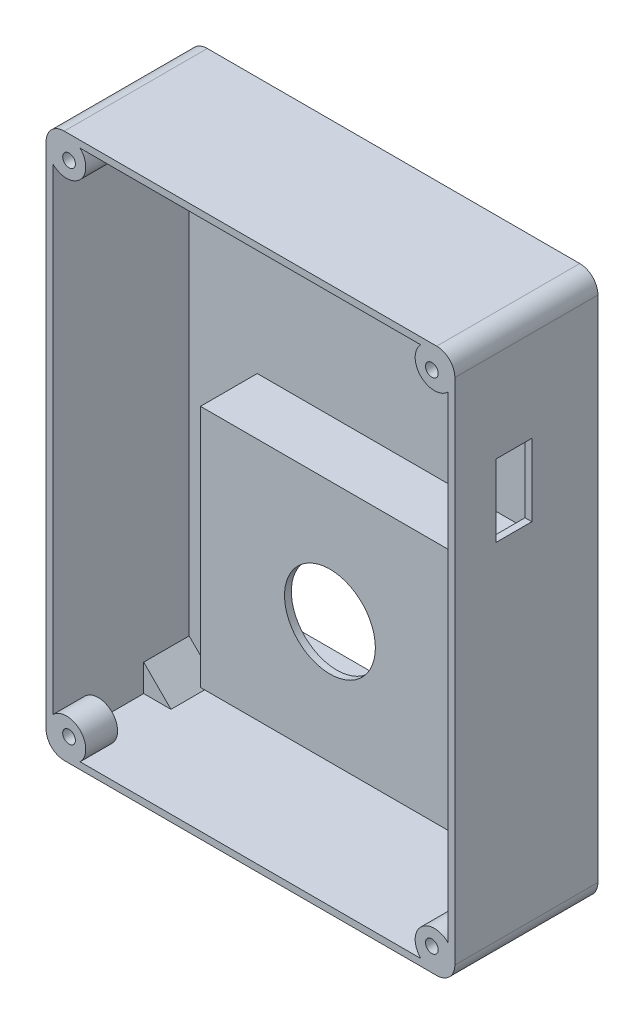
SolidWorks part; units mm, degrees
ref_plane "Front Plane" through (0, 0, 0) normal (0, 0, 1) x (1, 0, 0)
ref_plane "Top Plane" through (0, 0, 0) normal (0, 1, 0) x (1, 0, 0)
ref_plane "Right Plane" through (0, 0, 0) normal (1, 0, 0) x (0, 0, -1)
sketch "Sketch2" plane through (0, 0, 0) normal (0, 0, 1) x (1, 0, 0)
  line L1 (-45, -60) -> (45, -60)
  line L2 (-45, -60) -> (-45, 60)
  line L3 (-45, 60) -> (45, 60)
  line L4 (45, -60) -> (45, 60)
  line L5 (-45, -60) -> (45, 60) construction
  line L6 (-45, 60) -> (45, -60) construction
  point P0 (0, 0)
extrude "Boss-Extrude1" add sketch "Sketch2" along normal blind 31.5
sketch "Sketch4" plane through (0, 0, 31.5) normal (0, 0, 1) x (1, 0, 0)
  line L1 (-43.5, -58.5) -> (43.5, -58.5)
  line L2 (-43.5, -58.5) -> (-43.5, 58.5)
  line L3 (-43.5, 58.5) -> (43.5, 58.5)
  line L4 (43.5, -58.5) -> (43.5, 58.5)
  line L5 (-43.5, -58.5) -> (43.5, 58.5) construction
  line L6 (-43.5, 58.5) -> (43.5, -58.5) construction
  point P0 (0, 0)
extrude "Cut-Extrude1" cut sketch "Sketch4" against normal blind 30
fillet "Fillet4" radius 4 4 edges at (45, -60, 15.75) (-45, -60, 15.75) (45, 60, 15.75) (-45, 60, 15.75)
ref_plane "Plane1" through (0, 0, 0) normal (1, 0, 0) x (0, 0, -1)
ref_plane "Plane2" through (0, 0, 0) normal (0, 1, 0) x (1, 0, 0)
sketch "Sketch18" plane through (0, 0, 1.5) normal (0, 0, 1) x (1, 0, 0)
  line L0 (0, -58.5) -> (0, -48.5)
  line L1 (-43.5, -58.5) -> (43.5, -58.5) construction
  line L2 (0, -16.5) -> (0, 16.5) construction
  line L3 (0, -48.5) -> (0, -21.7755)
  line L5 (-28.5, -48.5755) -> (28.5, -48.5755)
  line L6 (-28.5, -48.5755) -> (-28.5, 5.0245)
  line L7 (-28.5, 5.0245) -> (28.5, 5.0245)
  line L8 (28.5, -48.5755) -> (28.5, 5.0245)
  line L9 (-28.5, -48.5755) -> (28.5, 5.0245) construction
  line L10 (-28.5, 5.0245) -> (28.5, -48.5755) construction
extrude "khay_pin" add sketch "Sketch18" along normal blind 12.5
sketch "Sketch21" plane through (0, 0, 14) normal (0, 0, 1) x (1, 0, 0)
  line L0 (-28.5, -21.7755) -> (28.5, -21.7755) construction
  line L1 (-28.5, -48.5755) -> (-28.5, 5.0245) construction
  line L2 (28.5, -48.5755) -> (28.5, 5.0245) construction
  line L4 (-26.5, -46.5755) -> (26.5, -46.5755)
  line L5 (-26.5, -46.5755) -> (-26.5, 3.0245)
  line L6 (-26.5, 3.0245) -> (26.5, 3.0245)
  line L7 (26.5, -46.5755) -> (26.5, 3.0245)
  line L8 (-26.5, -46.5755) -> (26.5, 3.0245) construction
  line L9 (-26.5, 3.0245) -> (26.5, -46.5755) construction
  point P6 (0, -21.7755)
extrude "Boss-Extrude11" add sketch "Sketch21" against normal blind 15
sketch "Sketch22" plane through (0, 0, -1) normal (0, 0, -1) x (-1, 0, 0)
  line L0 (-26.5, -21.7755) -> (26.5, -21.7755) construction
  line L1 (-26.5, -46.5755) -> (-26.5, 3.0245) construction
  line L2 (26.5, 3.0245) -> (26.5, -46.5755) construction
  line L4 (-26.5, -46.5755) -> (26.5, -46.5755)
  line L5 (-26.5, -46.5755) -> (-26.5, 3.0245)
  line L6 (-26.5, 3.0245) -> (26.5, 3.0245)
  line L7 (26.5, -46.5755) -> (26.5, 3.0245)
  line L8 (-26.5, -46.5755) -> (26.5, 3.0245) construction
  line L9 (-26.5, 3.0245) -> (26.5, -46.5755) construction
  point P6 (0, -21.7755)
extrude "Cut-Extrude4" cut sketch "Sketch22" against normal blind 13.5
sketch "Sketch30" plane through (26.5, 0, 0) normal (-1, 0, 0) x (0, 0, 1)
  line L0 (0, 3.0245) -> (12.5, 3.0245)
  line L1 (12.5, 3.0245) -> (12.5, -1.9755)
  line L2 (12.5, -1.9755) -> (12.5, -15.9755)
  line L3 (12.5, -1.9755) -> (5.5, -1.9755)
  line L4 (12.5, -15.9755) -> (5.5, -15.9755)
  line L5 (5.5, -1.9755) -> (5.5, -15.9755)
  line L6 (12.5, 3.0245) -> (12.5, -46.5755) construction
  line M3 (12.5, -46.5755) -> (12.5, 3.0245)
extrude "Cut-Extrude8" cut sketch "Sketch30" against normal blind 5 contours L3 L5 L4 M3
sketch "Sketch34" plane through (0, 0, 31.5) normal (0, 0, 1) x (1, 0, 0)
  line L0 (-43.5, 58.5) -> (-40.5, 58.5)
  line L1 (43.5, 58.5) -> (-43.5, 58.5) construction
  line L2 (-40.5, 58.5) -> (-40.5, 55.5)
  circle A0 centre (-40.5, 55.5) radius 4.2426
extrude "Boss-Extrude12" add sketch "Sketch34" against normal blind 7
sketch "Sketch37" plane through (45, 0, 0) normal (1, 0, 0) x (0, 0, -1)
  line L0 (-31.5, 56) -> (-31.5, 28)
  line L1 (-31.5, -56) -> (-31.5, 56) construction
  line L2 (-31.5, 28) -> (-18.5, 28)
  line L4 (-22.45, 20.05) -> (-14.55, 20.05)
  line L5 (-22.45, 20.05) -> (-22.45, 35.95)
  line L6 (-22.45, 35.95) -> (-14.55, 35.95)
  line L7 (-14.55, 20.05) -> (-14.55, 35.95)
  line L8 (-22.45, 20.05) -> (-14.55, 35.95) construction
  line L9 (-22.45, 35.95) -> (-14.55, 20.05) construction
extrude "Cut-Extrude10" cut sketch "Sketch37" against normal blind 5
mirror "Mirror1" about plane through (0, 0, 0) normal (1, 0, 0) of "Boss-Extrude12"
mirror "Mirror2" about plane through (0, 0, 0) normal (0, 1, 0) of "Mirror1", "Boss-Extrude12"
sketch "Sketch38" plane through (0, 0, 14) normal (0, 0, 1) x (1, 0, 0)
  line L0 (0, 5.0245) -> (0, -21.7755)
  line L1 (-28.5, 5.0245) -> (28.5, 5.0245) construction
  line L2 (0, -16.5) -> (0, 16.5) construction
  circle A0 centre (0, -21.7755) radius 10
extrude "Cut-Extrude11" cut sketch "Sketch38" against normal blind 10
sketch "Sketch40" plane through (0, 0, 0) normal (0, 0, -1) x (-1, 0, 0)
  line L0 (-26.5, 3.0245) -> (-29.5, 3.0245)
  line L1 (-29.5, 3.0245) -> (-29.5, -46.5755)
  line L2 (-29.5, 3.0245) -> (-35.5, 3.0245)
  line L3 (-29.5, -46.5755) -> (-35.5, -46.5755)
  line L4 (-35.5, 3.0245) -> (-35.5, -46.5755)
extrude "Boss-Extrude13" add sketch "Sketch40" along normal blind 5.8 contours L2 L4 L3 L1
mirror "Mirror3" about plane through (0, 0, 0) normal (1, 0, 0) of "Boss-Extrude13"
sketch "Sketch48" plane through (0, 0, 0) normal (0, 0, -1) x (-1, 0, 0)
  line L0 (-35.5, -46.5755) -> (35.5, -46.5755)
  line L1 (-35.5, -46.5755) -> (-35.5, -52.5755)
  line L2 (35.5, -46.5755) -> (35.5, -52.5755)
  line L3 (-35.5, -52.5755) -> (35.5, -52.5755)
extrude "Boss-Extrude14" add sketch "Sketch48" along normal blind 5.8
sketch "Sketch50" plane through (0, 3.0245, 0) normal (0, 1, 0) x (1, 0, 0)
  line L0 (29.5, 5.8) -> (29.5, 3.8)
  line L1 (29.5, 5.8) -> (29.5, 0) construction
  line L2 (29.5, 3.8) -> (31.8, 3.8)
  line L3 (31.8, 3.8) -> (31.8, 2)
  line L4 (31.8, 2) -> (29.5, 2)
  line L5 (29.5, 5.8) -> (29.5, 0) construction
  line L6 (29.5, 2) -> (29.5, 0)
  line L7 (29.5, 3.8) -> (31.8, 3.8)
  line L8 (29.5, 3.8) -> (29.5, 2)
  line L9 (31.8, 3.8) -> (31.8, 2)
  line L10 (29.5, 2) -> (31.8, 2)
  line M5 (29.5, 5.8) -> (29.5, 0)
extrude "Cut-Extrude14" cut sketch "Sketch50" against normal blind 49.6 contours L4 L3 L2 M5
mirror "Mirror7" about plane through (0, 0, 0) normal (1, 0, 0) of "Cut-Extrude14"
sketch "Sketch51" plane through (0, 0, 1.5) normal (0, 0, 1) x (1, 0, 0)
  line L0 (43.5, -52.5) -> (37.5, -58.5)
  line L1 (37.5, -58.5) -> (43.5, -58.5)
  line L2 (43.5, -58.5) -> (43.5, -52.5)
sketch "Sketch52" plane through (0, 0, 31.5) normal (0, 0, 1) x (1, 0, 0)
  line L0 (-43.8284, 58.8284) -> (-39.9393, 54.9393)
  arc A0 (-41, 60) -> (-45, 56) centre (-41, 56) ccw construction
  circle A1 centre (-39.9393, 54.9393) radius 1.4
extrude "Cut-Extrude15" cut sketch "Sketch52" against normal blind 10
mirror "Mirror9" about plane through (0, 0, 0) normal (1, 0, 0) of "Cut-Extrude15"
mirror "Mirror10" about plane through (0, 0, 0) normal (0, 1, 0) of "Mirror9", "Cut-Extrude15"
extrude "Boss-Extrude16" add sketch "Sketch51" along normal blind 10
mirror "Mirror11" about plane through (0, 0, 0) normal (1, 0, 0) of "Boss-Extrude16"
